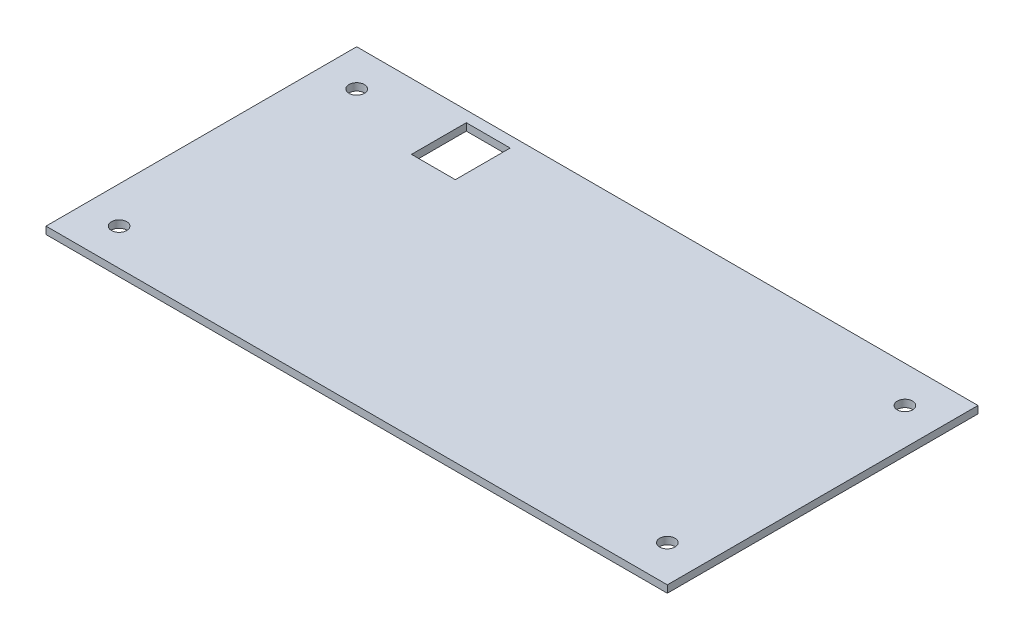
SolidWorks part; units mm, degrees
ref_plane "Front Plane" through (0, 0, 0) normal (0, 0, 1) x (1, 0, 0)
ref_plane "Top Plane" through (0, 0, 0) normal (0, 1, 0) x (1, 0, 0)
ref_plane "Right Plane" through (0, 0, 0) normal (1, 0, 0) x (0, 0, -1)
sketch "Sketch2" plane through (0, 0, 0) normal (0, 1, 0) x (1, 0, 0)
  line L1 (-74.5992, 39.4515) -> (95.4008, 39.4515)
  line L2 (-74.5992, 39.4515) -> (-74.5992, -45.5485)
  line L3 (-74.5992, -45.5485) -> (95.4008, -45.5485)
  line L4 (95.4008, 39.4515) -> (95.4008, -45.5485)
  dimension "D1" = 170
  dimension "D2" = 85
extrude "Boss-Extrude1" add sketch "Sketch2" along normal blind 2
sketch "Sketch3" plane through (0, 2, 0) normal (0, 1, 0) x (1, 0, 0)
  line L0 (-41.5992, 36.4515) -> (-41.5992, 21.4515)
  line L1 (95.4008, 39.4515) -> (-74.5992, 39.4515) construction
  line L3 (-29.5992, 36.4515) -> (-29.5992, 21.4515)
  line L4 (-74.5992, 39.4515) -> (-74.5992, -45.5485) construction
  line L5 (-41.5992, 36.4515) -> (-29.5992, 36.4515)
  line L6 (-41.5992, 21.4515) -> (-29.5992, 21.4515)
  point P14 (0, 0)
  dimension "D1" = 33
  dimension "D2" = 12
  dimension "D3" = 3
  dimension "D4" = 15
extrude "Cut-Extrude1" cut sketch "Sketch3" against normal through all
sketch "Sketch13" plane through (0, 2, 0) normal (0, 1, 0) x (1, 0, 0)
  line L0 (-74.5992, 39.4515) -> (-74.5992, -45.5485) construction
  line L1 (95.4008, -45.5485) -> (95.4008, 39.4515) construction
  line L2 (95.4008, 39.4515) -> (-74.5992, 39.4515) construction
  line L3 (-74.5992, -45.5485) -> (95.4008, -45.5485) construction
  circle A0 centre (-64.5992, 29.4515) radius 2.1
  circle A1 centre (85.4008, 29.4515) radius 2.1
  circle A2 centre (-64.5992, -35.5485) radius 2.1
  circle A3 centre (85.4008, -35.5485) radius 2.1
  point P10 (0, 0)
  dimension "D1" = 4.2
  dimension "D2" = 4.2
  dimension "D3" = 4.2
  dimension "D4" = 4.2
  dimension "D5" = 10
  dimension "D6" = 10
  dimension "D7" = 10
  dimension "D8" = 10
  dimension "D9" = 10
  dimension "D10" = 10
  dimension "D11" = 10
  dimension "D12" = 10
extrude "Cut-Extrude5" cut sketch "Sketch13" against normal through all
